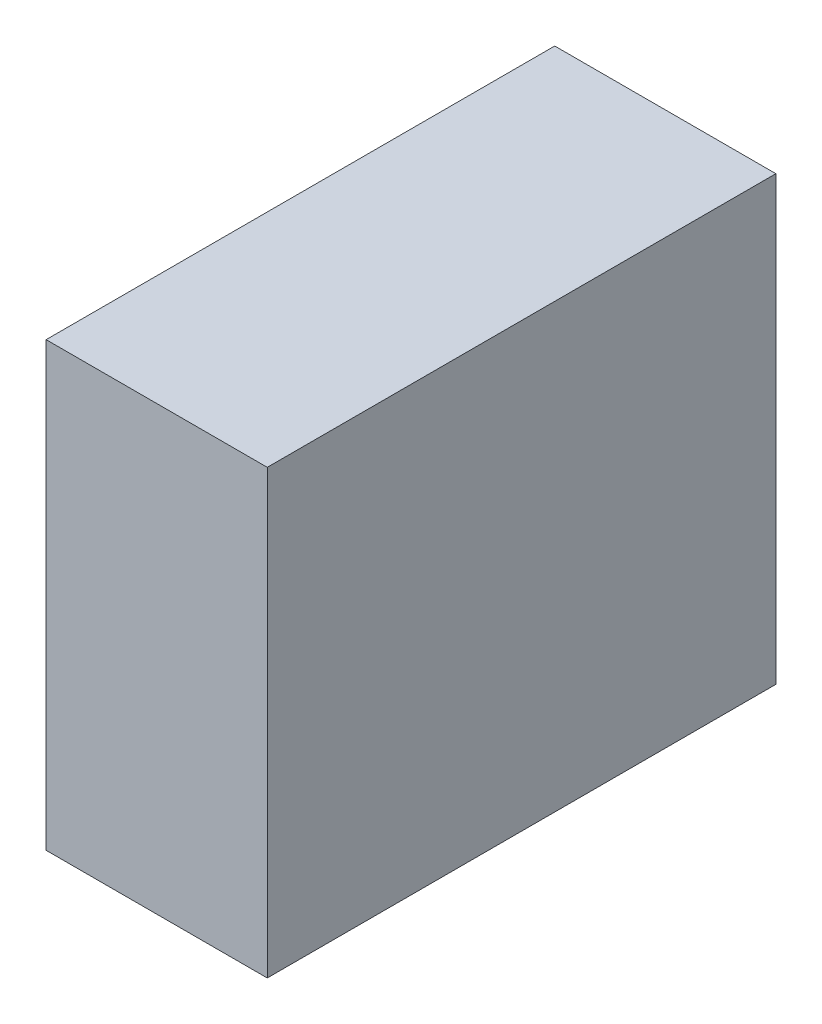
SolidWorks part; units mm, degrees
ref_plane "Front Plane" through (0, 0, 0) normal (0, 0, 1) x (1, 0, 0)
ref_plane "Top Plane" through (0, 0, 0) normal (0, 1, 0) x (1, 0, 0)
ref_plane "Right Plane" through (0, 0, 0) normal (1, 0, 0) x (0, 0, -1)
sketch "Sketch1" plane through (0, 0, 0) normal (1, 0, 0) x (0, 0, -1)
  line L1 (0, 0) -> (23, 0)
  line L2 (0, 0) -> (0, 20)
  line L3 (0, 20) -> (23, 20)
  line L4 (23, 0) -> (23, 20)
extrude "Boss-Extrude1" add sketch "Sketch1" against normal blind 10
